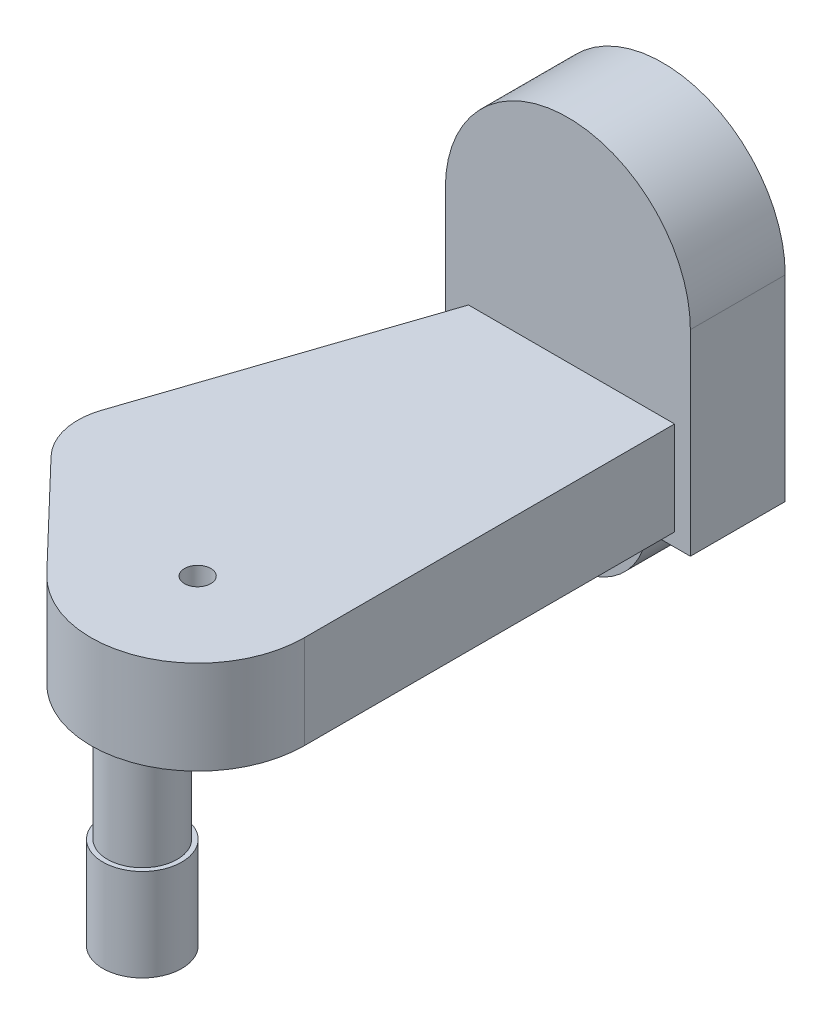
SolidWorks part; units mm, degrees
material "3.0205 (EN-AW 1200)"
ref_plane "Plan de face" through (0, 0, 0) normal (0, 0, 1) x (1, 0, 0)
ref_plane "Plan de dessus" through (0, 0, 0) normal (0, 1, 0) x (1, 0, 0)
ref_plane "Plan de droite" through (0, 0, 0) normal (1, 0, 0) x (0, 0, -1)
sketch "Esquisse1" plane through (0, 0, 0) normal (0, 0, 1) x (1, 0, 0)
  line L0 (53, -141) -> (85, -141)
  line L1 (85, 0) -> (85, -141)
  line L2 (0, 100.7168) -> (0, -197.7461) construction
  line L3 (-53, -141) -> (-85, -141)
  line L4 (-85, 0) -> (-85, -141)
  arc A0 (85, 0) -> (-85, 0) centre (0, 0) ccw
  arc A1 (-53, -141) -> (53, -141) centre (0, -141) ccw
  dimension "D2" = 85
  dimension "D3" = 106
  dimension "D1" = 141
extrude "Extrusion1" add sketch "Esquisse1" along normal blind 64
shell "Coque14" thickness 8
ref_plane "Plan1" through (0, -139, 0) normal (0, 1, 0) x (-1, 0, 0)
sketch "Esquisse2" plane through (0, -139, 0) normal (0, 1, 0) x (-1, 0, 0)
  line L0 (-81, 72) -> (-81, 353)
  line L7 (0, 64) -> (0, 0) construction
  line L8 (58.4615, 409.0647) -> (134.3656, 329.9157)
  line L9 (145.4451, 280.3841) -> (75.3817, 72)
  line L10 (93, 72) -> (-93, 72) construction
  line L11 (75.3817, 72) -> (-81, 72)
  arc A0 (58.4615, 409.0647) -> (-81, 353) centre (0, 353) ccw
  arc A1 (145.4451, 280.3841) -> (134.3656, 329.9157) centre (99, 296) ccw
  dimension "D1" = 162
  dimension "D2" = 98
  dimension "D3" = 81
  dimension "D4" = 99
  dimension "D5" = 57
  dimension "D6" = 281
extrude "Extrusion2" add sketch "Esquisse2" along normal blind 71
ref_plane "Plan2" through (-53, -141, 64) normal (0, -1, 0) x (1, 0, 0)
sketch "Esquisse4" plane through (-53, -141, 64) normal (0, -1, 0) x (1, 0, 0)
  line L2 (101.5, 8) -> (101.5, 173)
  line L3 (101.5, 173) -> (53, 188)
  line L4 (53, -5.8608) -> (53, 225.4809) construction
  line L5 (53, 0) -> (53, -64) construction
  line L6 (4.5, 173) -> (53, 188)
  line L7 (4.5, 8) -> (4.5, 173)
  line L8 (113.4731, 8) -> (-7.4731, 8) construction
  line L9 (101.5, 8) -> (4.5, 8)
  point P12 (53, 0)
  dimension "D1" = 48.5
  dimension "D2" = 165
  dimension "D3" = 15
extrude "Enlèv. mat.-Extru.1" cut sketch "Esquisse4" against normal blind 65
sketch "Esquisse8" plane through (0, -139, 0) normal (0, -1, 0) x (1, 0, 0)
  circle A0 centre (-99, 296) radius 26.5
  arc A1 (-134.3656, 329.9157) -> (-145.4451, 280.3841) centre (-99, 296) ccw construction
  dimension "D1" = 53
extrude "Extrusion3" add sketch "Esquisse8" along normal blind 84
sketch "Esquisse9" plane through (0, -223, 0) normal (0, -1, 0) x (1, 0, 0)
  circle A0 centre (-99, 296) radius 34.5
  circle A1 centre (-99, 296) radius 26.5 construction
  dimension "D1" = 69
extrude "Extrusion4" add sketch "Esquisse9" along normal blind 14
sketch "Esquisse10" plane through (0, -237, 0) normal (0, -1, 0) x (1, 0, 0)
  circle A0 centre (-99, 296) radius 26.5
  circle A1 centre (-99, 296) radius 34.5 construction
  dimension "D1" = 53
extrude "Extrusion5" add sketch "Esquisse10" along normal blind 82
sketch "Esquisse11" plane through (0, -319, 0) normal (0, -1, 0) x (1, 0, 0)
  circle A0 centre (-99, 296) radius 30
  circle A1 centre (-99, 296) radius 26.5 construction
  dimension "D1" = 60
extrude "Extrusion6" add sketch "Esquisse11" along normal blind 70
sketch "Esquisse12" plane through (0, 0, 72) normal (0, 0, 1) x (1, 0, 0)
  circle A0 centre (0, -141) radius 25
  arc A1 (-60.4731, -149) -> (60.4731, -149) centre (0, -141) ccw construction
  dimension "D1" = 50
extrude "Extrusion7" add sketch "Esquisse12" along normal blind 110
sketch "Esquisse13" plane through (0, 0, 182) normal (0, 0, 1) x (1, 0, 0)
  circle A0 centre (0, -141) radius 17.5
  circle A1 centre (0, -141) radius 25 construction
  dimension "D1" = 35
extrude "Extrusion8" add sketch "Esquisse13" along normal blind 50
sketch "Esquisse14" plane through (0, -139, 0) normal (0, -1, 0) x (1, 0, 0)
  circle A0 centre (0, 353) radius 10
  arc A1 (81, 353) -> (-58.4615, 409.0647) centre (0, 353) ccw construction
  dimension "D2" = 20
extrude "Enlèv. mat.-Extru.2" cut sketch "Esquisse14" against normal through all
